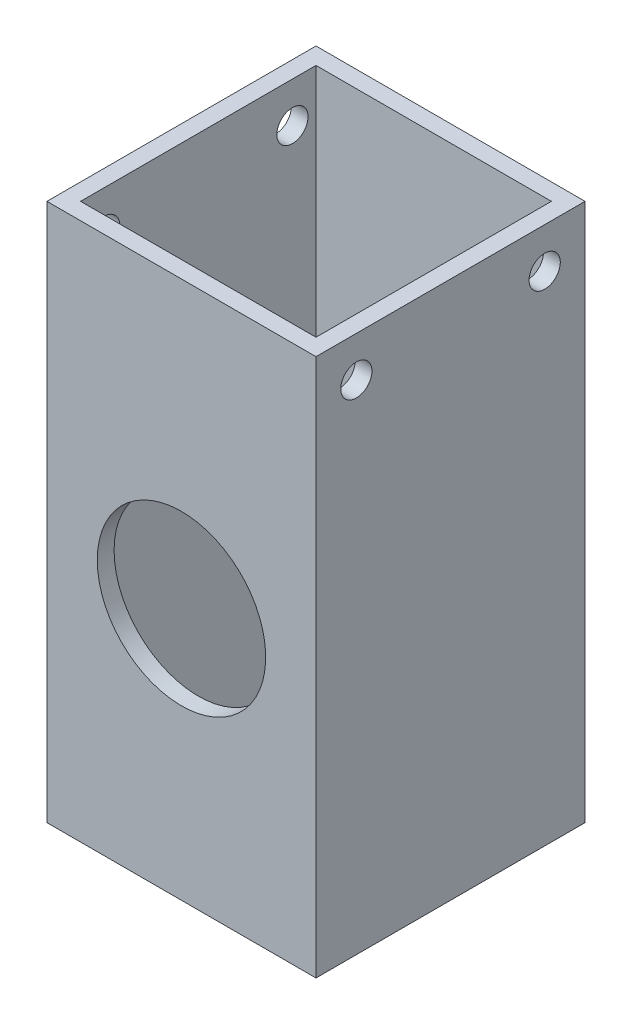
SolidWorks part; units mm, degrees
ref_plane "Front Plane" through (0, 0, 0) normal (0, 0, 1) x (1, 0, 0)
ref_plane "Top Plane" through (0, 0, 0) normal (0, 1, 0) x (1, 0, 0)
ref_plane "Right Plane" through (0, 0, 0) normal (1, 0, 0) x (0, 0, -1)
sketch "Sketch1" plane through (0, 0, 0) normal (0, 1, 0) x (1, 0, 0)
  line L0 (11.1125, 11.1125) -> (-11.1125, 11.1125)
  line L1 (12.7, 12.7) -> (-12.7, 12.7)
  line L2 (-12.7, 12.7) -> (-12.7, -12.7)
  line L3 (-12.7, -12.7) -> (12.7, -12.7)
  line L4 (12.7, -12.7) -> (12.7, 12.7)
  line L5 (-11.1125, 11.1125) -> (-11.1125, -11.1125)
  line L6 (-11.1125, -11.1125) -> (11.1125, -11.1125)
  line L7 (11.1125, -11.1125) -> (11.1125, 11.1125)
  circle A0 centre (0, 0) radius 12.7 construction
  dimension "D1" = 25.4
  dimension "D2" = 1.5875
extrude "Boss-Extrude1" add sketch "Sketch1" along normal blind 50.8
sketch "Sketch2" plane through (0, 0, 12.7) normal (0, 0, 1) x (1, 0, 0)
  line L2 (0, 23.8506) -> (0, 0) construction
  line L3 (12.7, 50.8) -> (12.7, 0) construction
  circle A0 centre (0, 23.8506) radius 7.9502
  dimension "D1" = 15.9004
  dimension "D2" = 23.8506
extrude "Cut-Extrude1" cut sketch "Sketch2" against normal through all both and the other way through all
sketch "Sketch3" plane through (12.7, 0, 0) normal (1, 0, 0) x (0, 0, -1)
  line L0 (-8.89, 46.99) -> (-8.89, 50.8) construction
  line L1 (-12.7, 50.8) -> (12.7, 50.8) construction
  line L2 (-8.89, 46.99) -> (-12.7, 46.99) construction
  line L3 (-12.7, 50.8) -> (-12.7, 0) construction
  line L4 (0, 55) -> (0, -55) construction
  circle A0 centre (-8.89, 46.99) radius 1.4732
  circle A1 centre (8.89, 46.99) radius 1.4732
  dimension "D1" = 2.9464
  dimension "D2" = 3.81
  dimension "D3" = 3.81
extrude "Cut-Extrude2" cut sketch "Sketch3" against normal through all both and the other way through all
equation "\"diameter\"= .626in"
equation "\"D1@Sketch2\"=\"diameter\""
equation "\"D2@Sketch2\"=1.5*\"diameter\""
equation "\"bolt_diam\"= .1160in"
equation "\"D1@Sketch3\"=\"bolt_diam\""
equation "\"D2@Sketch3\"=\"padding\""
equation "\"padding\"= .15in"
equation "\"D3@Sketch3\"=\"padding\""
equation "\"D1@Boss-Extrude1\"=2"
